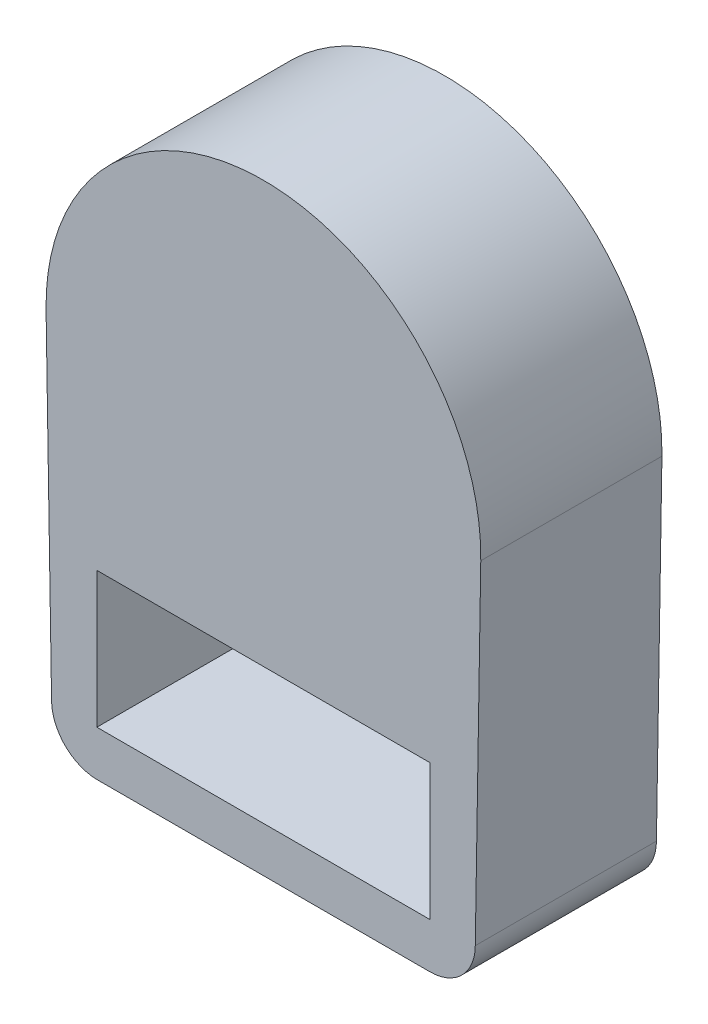
SolidWorks part; units mm, degrees
ref_plane "Plano frontal" through (0, 0, 0) normal (0, 0, 1) x (1, 0, 0)
ref_plane "Plano superior" through (0, 0, 0) normal (0, 1, 0) x (1, 0, 0)
ref_plane "Plano direito" through (0, 0, 0) normal (1, 0, 0) x (0, 0, -1)
sketch "Sketch1" plane through (0, 0, 0) normal (0, 0, 1) x (1, 0, 0)
  line L0 (-18.39, -12.5) -> (18.39, -12.5)
  line L1 (-18.39, 7.5) -> (18.39, 7.5)
  line L2 (-18.39, 7.5) -> (-18.39, -7.5)
  line L3 (-18.39, -7.5) -> (18.39, -7.5)
  line L4 (18.39, 7.5) -> (18.39, -7.5)
  line L5 (-18.39, 7.5) -> (18.39, -7.5) construction
  line L6 (-18.39, -7.5) -> (18.39, 7.5) construction
  line L10 (-23.39, 12.5) -> (23.39, 12.5) construction
  line L11 (-23.39, -12.5) -> (23.39, -12.5) construction
  line L12 (-23.39, 12.5) -> (-23.39, -12.5) construction
  line L13 (23.39, 12.5) -> (23.39, -12.5) construction
  line L15 (-23.9968, 29.6076) -> (-23.39, -7.5)
  line L16 (23.9968, 29.6076) -> (23.39, -7.5)
  circle A2 centre (0, 30) radius 19
  arc A3 (23.9968, 29.6076) -> (-23.9968, 29.6076) centre (0, 30) ccw
  arc A4 (-18.39, -12.5) -> (-23.39, -7.5) centre (-18.39, -7.5) cw
  arc A5 (18.39, -12.5) -> (23.39, -7.5) centre (18.39, -7.5) ccw
  point P0 (0, 0)
  dimension "D1" = 36.78
  dimension "D2" = 15
  dimension "D3" = 5
extrude "Boss-Extrude1" add sketch "Sketch1" along normal blind 15
sketch "Sketch13" plane through (0, 0, 15) normal (0, 0, 1) x (1, 0, 0)
  line L0 (-23.39, -7.5) -> (-23.9968, 29.6076)
  line L1 (-18.39, -12.5) -> (18.39, -12.5)
  line L2 (23.39, -7.5) -> (23.9968, 29.6076)
  line L3 (-18.39, 7.5) -> (18.39, 7.5)
  line L4 (18.39, 7.5) -> (18.39, -7.5)
  line L5 (18.39, -7.5) -> (-18.39, -7.5)
  line L6 (-18.39, -7.5) -> (-18.39, 7.5)
  line L7 (0, 7.5) -> (0, 30)
  line L8 (0, 11) -> (0, 7.5)
  circle A1 centre (0, 30) radius 19 construction
  arc A3 (23.9968, 29.6076) -> (-23.9968, 29.6076) centre (0, 30) ccw
  arc A4 (-23.39, -7.5) -> (-18.39, -12.5) centre (-18.3069, -7.4169) ccw
  arc A5 (18.39, -12.5) -> (23.39, -7.5) centre (18.39, -7.5) ccw
  dimension "D1" = 22.5
  dimension "D2" = 48
extrude "Boss-Extrude4" add sketch "Sketch13" along normal blind 5
